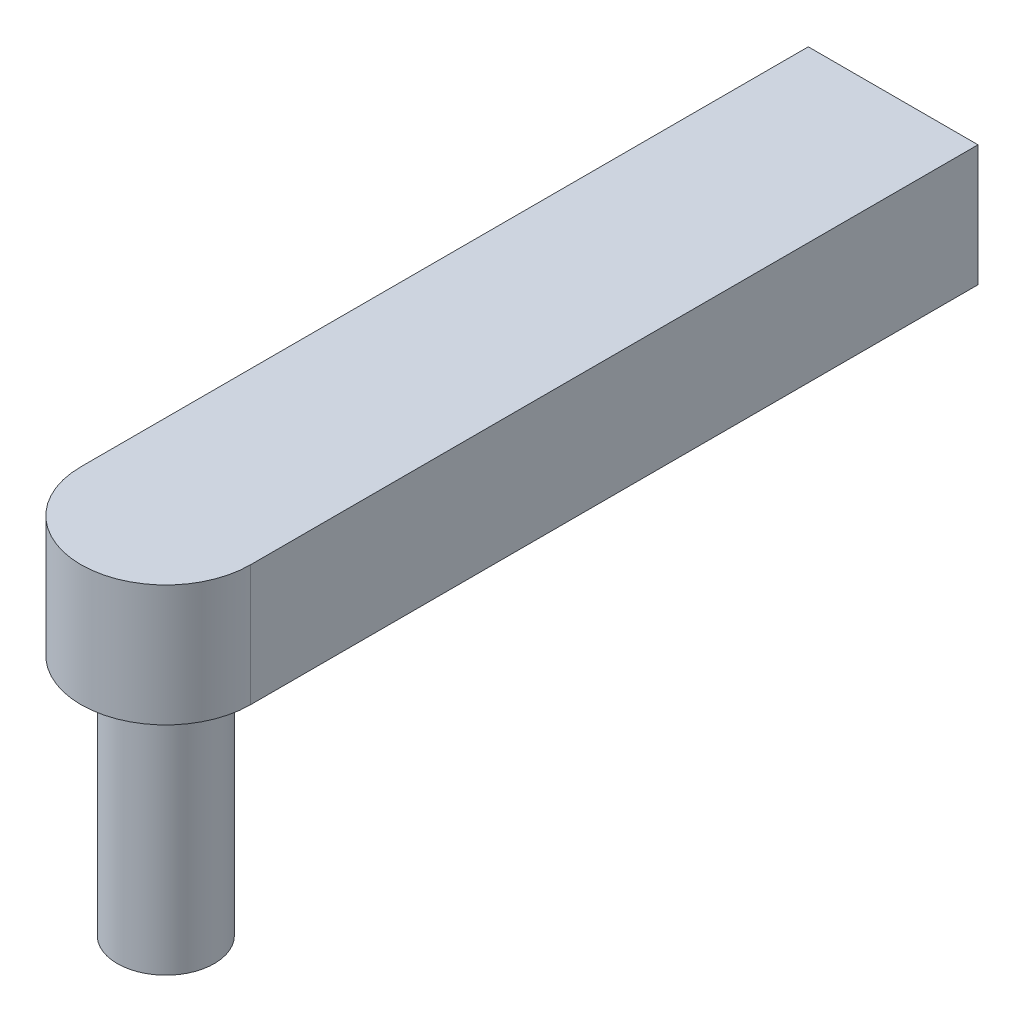
SolidWorks part; units mm, degrees
ref_plane "Спереди" through (0, 0, 0) normal (0, 0, 1) x (1, 0, 0)
ref_plane "Сверху" through (0, 0, 0) normal (0, 1, 0) x (1, 0, 0)
ref_plane "Справа" through (0, 0, 0) normal (1, 0, 0) x (0, 0, -1)
sketch "Эскиз1" plane through (0, 0, 0) normal (0, 1, 0) x (1, 0, 0)
  circle A0 centre (0, 0) radius 2
extrude "Бобышка-Вытянуть1" add sketch "Эскиз1" along normal blind 10
sketch "Эскиз2" plane through (0, 10, 0) normal (0, 1, 0) x (1, 0, 0)
  line L0 (-3.5, 0) -> (-3.5, 30)
  line L1 (3.5, 0) -> (3.5, 30)
  line L2 (-3.5, 30) -> (3.5, 30)
  arc A0 (-3.5, 0) -> (3.5, 0) centre (0, 0) ccw
extrude "Бобышка-Вытянуть2" add sketch "Эскиз2" along normal blind 5
